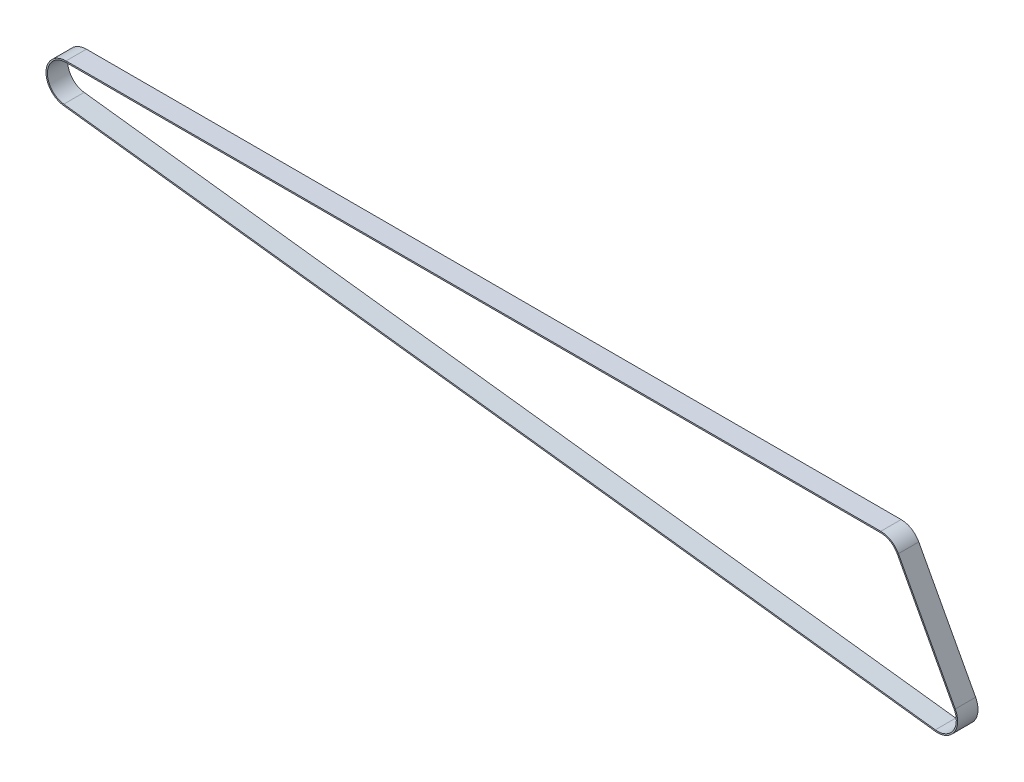
SolidWorks part; units mm, degrees
ref_plane "Ebene vorne" through (0, 0, 0) normal (0, 0, 1) x (1, 0, 0)
ref_plane "Ebene oben" through (0, 0, 0) normal (0, 1, 0) x (1, 0, 0)
ref_plane "Ebene rechts" through (0, 0, 0) normal (1, 0, 0) x (0, 0, -1)
sketch "Skizze1" plane through (0, 0, 0) normal (0, 0, 1) x (1, 0, 0)
  line L0 (-240, 0) -> (240, 0) construction
  line L1 (240, 0) -> (240, -62.5) construction
  line L2 (240, -62.5) -> (273.5, -62.5) construction
  line L3 (-240, 11) -> (240, 11)
  line L4 (249.6951, 5.1966) -> (283.1951, -57.3034)
  line L5 (-241.329, -10.9194) -> (272.171, -73.4194)
  circle A0 centre (273.5, -62.5) radius 11 construction
  circle A1 centre (240, 0) radius 11 construction
  circle A2 centre (-240, 0) radius 11 construction
  arc A3 (283.1951, -57.3034) -> (272.171, -73.4194) centre (273.5, -62.5) cw
  arc A4 (240, 11) -> (249.6951, 5.1966) centre (240, 0) cw
  arc A5 (-241.329, -10.9194) -> (-240, 11) centre (-240, 0) cw
  dimension "D4" = 22
  dimension "D1" = 480
  dimension "D2" = 62.5
  dimension "D3" = 33.5
extrude "Linear-Austragen-Dünn1" add sketch "Skizze1" along normal mid plane 12 thin thin type one direction wall 0.8
sketch "Skizze2" plane through (0, 0, 0) normal (0, 0, 1) x (1, 0, 0)
  line L0 (-240, 11) -> (240, 11) construction
  line L1 (-131, 8.7431) -> (-119.2321, 8.7431)
  line L2 (-119.2321, 8.7431) -> (-114.1057, 8.0923)
  line L3 (-131, 11) -> (-129.5811, 11.8468)
  line L4 (-129.5811, 11.8468) -> (-116.2454, 12.7313)
  circle A0 centre (-131, 9.8715) radius 1.1285 construction
  arc A1 (-131, 8.7431) -> (-131, 11) centre (-131, 9.8715) cw
  dimension "D1" = 109
extrude "Linear-Austragen-Dünn2" [suppressed] add sketch "Skizze2" along normal mid plane 12 thin
